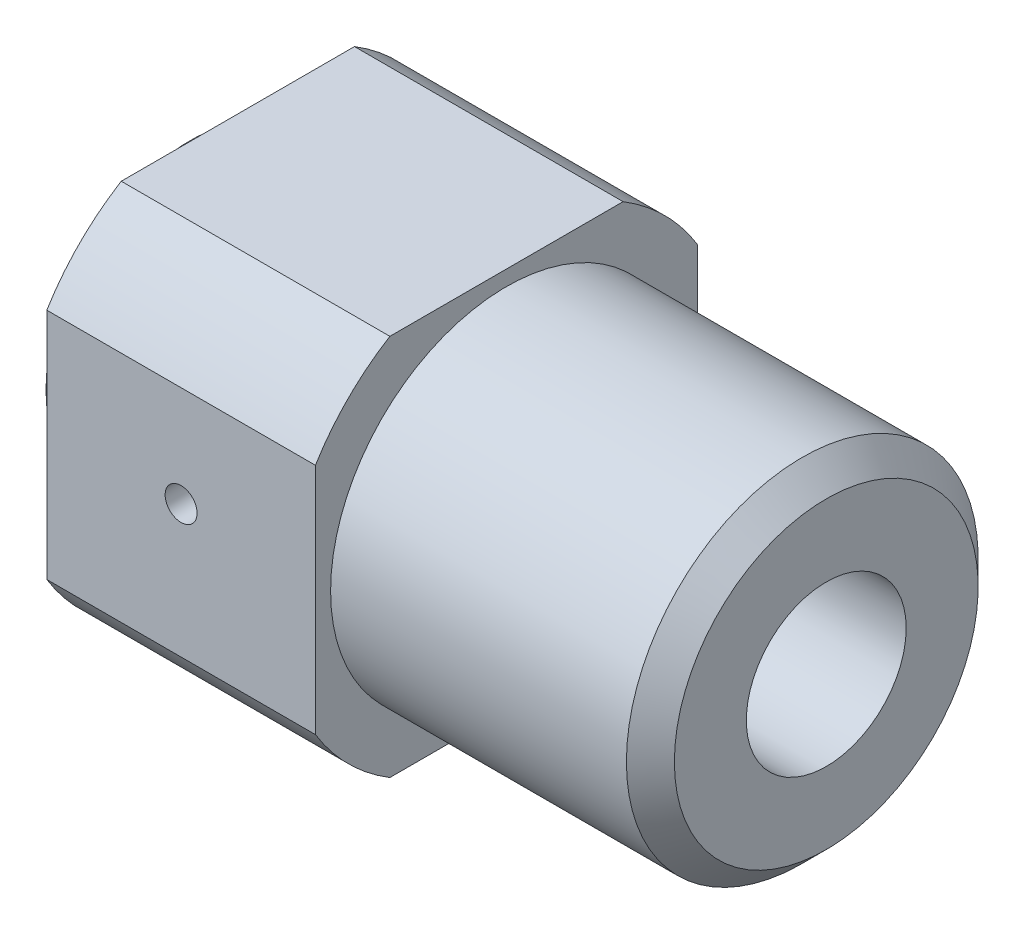
SolidWorks part; units mm, degrees
ref_plane "Alzado" through (0, 0, 0) normal (0, 0, 1) x (1, 0, 0)
ref_plane "Planta" through (0, 0, 0) normal (0, 1, 0) x (1, 0, 0)
ref_plane "Vista lateral" through (0, 0, 0) normal (1, 0, 0) x (0, 0, -1)
sketch "Croquis1" plane through (0, 0, 0) normal (0, 1, 0) x (1, 0, 0)
  line L0 (0, 0) -> (36.8, 0)
  line L1 (36.8, 0) -> (36.8, 9.5)
  line L2 (36.8, 9.5) -> (35.3, 11)
  line L3 (35.3, 11) -> (16.8, 11)
  line L4 (16.8, 11) -> (16.8, 14)
  line L5 (16.8, 14) -> (0, 14)
  line L6 (0, 14) -> (0, 0)
  dimension "D1" = 36.8
  dimension "D2" = 14
  dimension "D3" = 9.5
  dimension "D4" = 16.8
  dimension "D5" = 3
  dimension "D6" = 18.5
revolve "Revolución1" add sketch "Croquis1" angle 360 about L0
sketch "Croquis2" plane through (0, 0, 0) normal (1, 0, 0) x (0, 0, -1)
  line L1 (11.95, -11.95) -> (-11.95, -11.95)
  line L2 (11.95, -11.95) -> (11.95, 11.95)
  line L3 (11.95, 11.95) -> (-11.95, 11.95)
  line L4 (-11.95, -11.95) -> (-11.95, 11.95)
  line L5 (11.95, -11.95) -> (-11.95, 11.95) construction
  line L6 (11.95, 11.95) -> (-11.95, -11.95) construction
  point P0 (0, 0)
  dimension "D1" = 23.9
extrude "Cortar-Extruir1" cut sketch "Croquis2" along normal through all flip side to cut
sketch "Croquis3" plane through (0, 0, 11.95) normal (0, 0, 1) x (1, 0, 0)
  line L0 (0, 7.2937) -> (16.8, 7.2937) construction
  line L2 (0, 7.2937) -> (0, -7.2937) construction
  circle A0 centre (8.4, 0.9937) radius 1
  dimension "D1" = 2
  dimension "D2" = 6.3
  dimension "D3" = 8.4
sketch "Croquis4" plane through (36.8, 0, 0) normal (1, 0, 0) x (0, 0, -1)
  circle A0 centre (0, 0) radius 5
  dimension "D1" = 10
extrude "Cortar-Extruir2" cut sketch "Croquis4" against normal through all
extrude "Cortar-Extruir3" cut sketch "Croquis3" against normal blind 13 contours A0
sketch "Croquis5" plane through (0, 0, 0) normal (-1, 0, 0) x (0, 0, 1)
  circle A0 centre (0, 0) radius 9
  circle A1 centre (0, 0) radius 5
  dimension "D1" = 18
extrude "Saliente-Extruir1" add sketch "Croquis5" along normal blind 3
